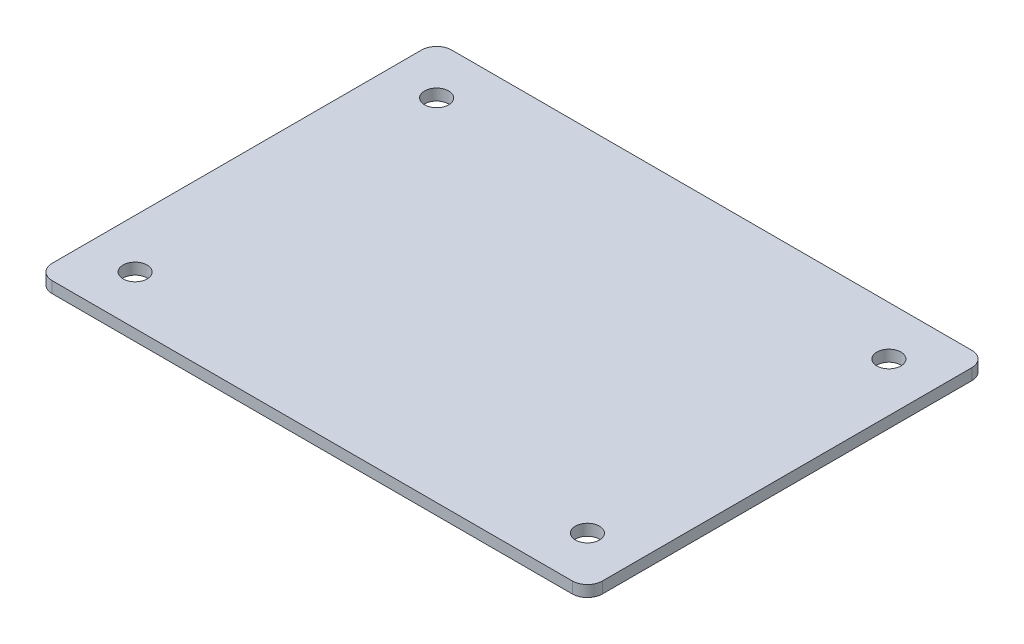
SolidWorks part; units mm, degrees
ref_plane "前视基准面" through (0, 0, 0) normal (0, 0, 1) x (1, 0, 0)
ref_plane "上视基准面" through (0, 0, 0) normal (0, 1, 0) x (1, 0, 0)
ref_plane "右视基准面" through (0, 0, 0) normal (1, 0, 0) x (0, 0, -1)
sketch "草图1" plane through (0, 0, 0) normal (0, 1, 0) x (1, 0, 0)
  line L1 (36.5, -26.5) -> (-36.5, -26.5)
  line L2 (36.5, -26.5) -> (36.5, 26.5)
  line L3 (36.5, 26.5) -> (-36.5, 26.5)
  line L4 (-36.5, -26.5) -> (-36.5, 26.5)
  line L5 (36.5, -26.5) -> (-36.5, 26.5) construction
  line L6 (36.5, 26.5) -> (-36.5, -26.5) construction
  point P0 (0, 0)
  dimension "D1" = 73
  dimension "D2" = 53
extrude "凸台-拉伸1" add sketch "草图1" along normal blind 1.5
fillet "圆角1" radius 2 4 edges at (-36.5, 0.75, -26.5) (36.5, 0.75, -26.5) (36.5, 0.75, 26.5) (-36.5, 0.75, 26.5)
sketch "草图2" plane through (0, 1.5, 0) normal (0, 1, 0) x (1, 0, 0)
  line L1 (30, -20) -> (-30, -20) construction
  line L2 (30, -20) -> (30, 20) construction
  line L3 (30, 20) -> (-30, 20) construction
  line L4 (-30, -20) -> (-30, 20) construction
  line L5 (30, -20) -> (-30, 20) construction
  line L6 (30, 20) -> (-30, -20) construction
  circle A0 centre (-30, 20) radius 1.6
  point P0 (0, 0)
  dimension "D3" = 3.2
  dimension "D1" = 60
  dimension "D2" = 40
extrude "切除-拉伸1" cut sketch "草图2" against normal through all
pattern_linear "阵列(线性)1" count 2 spacing 60 along (1, 0, 0) count 2 spacing 40 along (0, 0, 1) of "切除-拉伸1"
